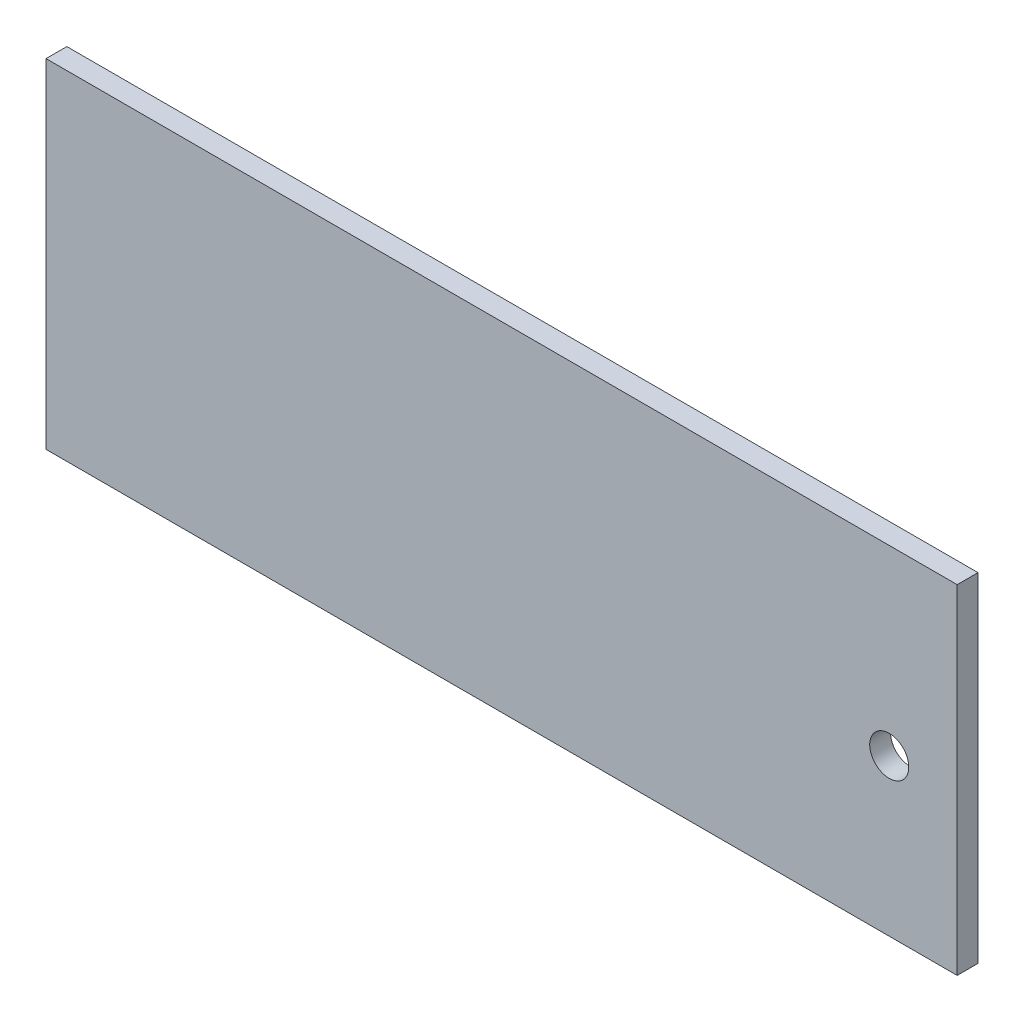
SolidWorks part; units mm, degrees
material "Rubber"
ref_plane "Front Plane" through (0, 0, 0) normal (0, 0, 1) x (1, 0, 0)
ref_plane "Top Plane" through (0, 0, 0) normal (0, 1, 0) x (1, 0, 0)
ref_plane "Right Plane" through (0, 0, 0) normal (1, 0, 0) x (0, 0, -1)
sketch "Sketch1" plane through (0, 0, 0) normal (0, 0, 1) x (1, 0, 0)
  line L1 (0, 0) -> (35, 0)
  line L2 (0, 0) -> (0, 13)
  line L3 (0, 13) -> (35, 13)
  line L4 (35, 0) -> (35, 13)
  circle A0 centre (32.39, 6) radius 0.75
  dimension "D3" = 1.5
  dimension "D4" = 6
  dimension "D5" = 2.61
  dimension "D1" = 13
  dimension "D2" = 35
extrude "Boss-Extrude1" add sketch "Sketch1" along normal blind 0.8
